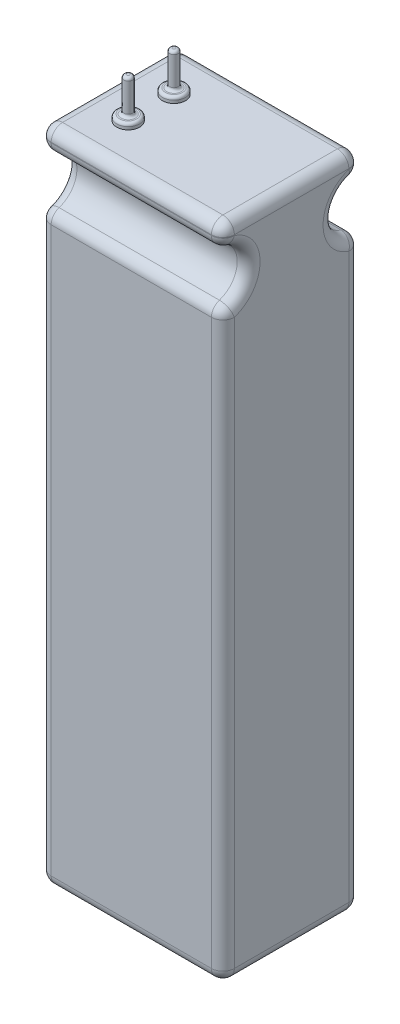
SolidWorks part; units mm, degrees
ref_plane "Front Plane" through (0, 0, 0) normal (0, 0, 1) x (1, 0, 0)
ref_plane "Top Plane" through (0, 0, 0) normal (0, 1, 0) x (1, 0, 0)
ref_plane "Right Plane" through (0, 0, 0) normal (1, 0, 0) x (0, 0, -1)
sketch "Sketch1" plane through (0, 0, 0) normal (0, 1, 0) x (1, 0, 0)
  line L1 (-16, -12) -> (16, -12)
  line L2 (-16, -12) -> (-16, 12)
  line L3 (-16, 12) -> (16, 12)
  line L4 (16, -12) -> (16, 12)
  line L5 (-16, -12) -> (16, 12) construction
  line L6 (-16, 12) -> (16, -12) construction
  point P0 (0, 0)
  dimension "D1" = 24
  dimension "D2" = 32
extrude "Boss-Extrude1" add sketch "Sketch1" along normal blind 115
sketch "Sketch2" plane through (-16, 0, 0) normal (-1, 0, 0) x (0, 0, 1)
  line L0 (12, 115) -> (12, 0) construction
  line L1 (-12, 115) -> (-12, 0) construction
  circle A0 centre (12, 106.6968) radius 4.5
  circle A1 centre (-12, 106.6968) radius 4.5
extrude "Cut-Extrude1" cut sketch "Sketch2" against normal blind 40
fillet "Fillet1" radius 2 2 edges at (0, 111.1968, 12) (0, 102.1968, 12)
fillet "Fillet2" radius 2 5 edges at (-16, 113.9407, 12) (-16, 111.7048, 11.6172) (-16, 50.2561, 12) (-16, 101.6889, 11.6172) (-16, 106.6968, 7.5)
fillet "Fillet3" radius 2 5 edges at (-16, 113.0984, -12) (-16, 106.6968, -7.5) (-16, 51.0984, -12) (0, 102.1968, -12) (0, 111.1968, -12)
fillet "Fillet4" radius 2 10 edges at (16, 50.2561, -12) (16, 101.6889, -11.6172) (16, 113.9407, -12) (16, 111.7048, -11.6172) (16, 113.9407, 12) (16, 111.7048, 11.6172) (16, 50.2561, 12) (16, 101.6889, 11.6172) (16, 106.6968, -7.5) (16, 106.6968, 7.5)
fillet "Fillet5" radius 2 8 edges at (-15.4142, 0, -11.4142) (-16, 0, 0) (-15.4142, 0, 11.4142) (0, 0, 12) (15.4142, 0, 11.4142) (16, 0, 0) (15.4142, 0, -11.4142) (0, 0, -12)
fillet "Fillet6" radius 2 8 edges at (15.4142, 115, 11.4142) (0, 115, 12) (-15.4142, 115, 11.4142) (-16, 115, 0) (-15.4142, 115, -11.4142) (0, 115, -12) (15.4142, 115, -11.4142) (16, 115, 0)
sketch "Sketch3" plane through (0, 115, 0) normal (0, 1, 0) x (1, 0, 0)
  circle A0 centre (-8.5417, -4) radius 2
  circle A1 centre (-8.5417, 4) radius 2
  dimension "D1" = 8
  dimension "D2" = 4
extrude "Boss-Extrude2" add sketch "Sketch3" along normal blind 1
sketch "Sketch4" plane through (0, 115, 0) normal (0, 1, 0) x (1, 0, 0)
  circle A0 centre (-8.5417, -4) radius 0.75
  circle A1 centre (-8.5417, 4) radius 0.75
extrude "Boss-Extrude3" add sketch "Sketch4" along normal blind 7
fillet "Fillet7" radius 0.5 2 edges at (-8.5417, 116, 6) (-8.5417, 116, -2)
fillet "Fillet8" radius 0.5 4 edges at (-8.5417, 122, -3.25) (-8.5417, 122, 4.75) (-8.5417, 116, 4.75) (-8.5417, 116, -3.25)
